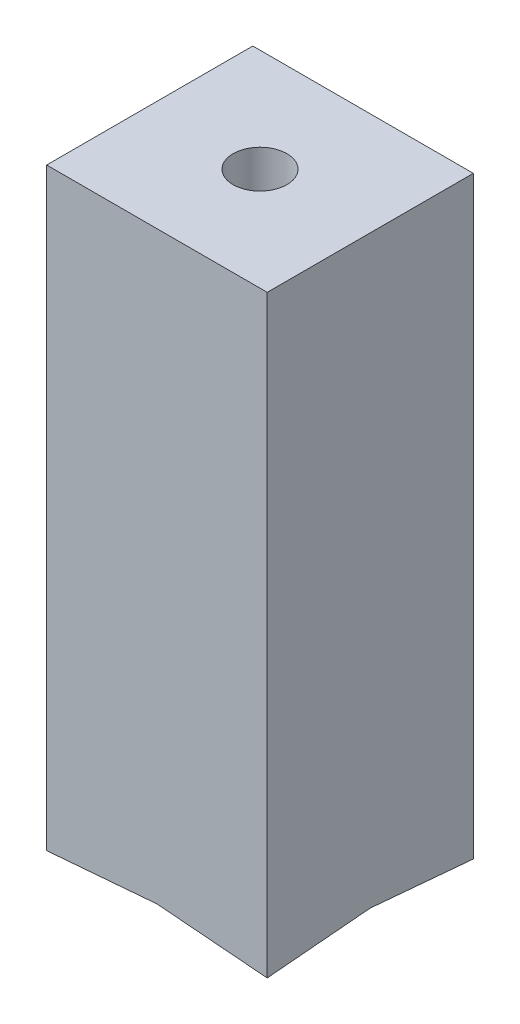
SolidWorks part; units mm, degrees
material "K110"
ref_plane "Front Plane" through (0, 0, 0) normal (0, 0, 1) x (1, 0, 0)
ref_plane "Top Plane" through (0, 0, 0) normal (0, 1, 0) x (1, 0, 0)
ref_plane "Right Plane" through (0, 0, 0) normal (1, 0, 0) x (0, 0, -1)
sketch "Sketch1" plane through (0, 0, 0) normal (0, 1, 0) x (1, 0, 0)
  line L1 (-10.25, -9.58) -> (10.25, -9.58)
  line L2 (-10.25, -9.58) -> (-10.25, 9.58)
  line L3 (-10.25, 9.58) -> (10.25, 9.58)
  line L4 (10.25, -9.58) -> (10.25, 9.58)
  line L5 (-10.25, -9.58) -> (10.25, 9.58) construction
  line L6 (-10.25, 9.58) -> (10.25, -9.58) construction
  point P0 (0, 0)
  dimension "D1" = 19.16
  dimension "D2" = 20.5
extrude "Boss-Extrude1" add sketch "Sketch1" against normal blind 55.2
sketch "Sketch5" plane through (10.25, 0, 0) normal (1, 0, 0) x (0, 0, -1)
  line L0 (-9.58, -55.2) -> (0, -54.3619)
  line L1 (0, -54.3619) -> (9.58, -55.2)
  line L2 (9.58, -55.2) -> (-9.58, -55.2)
  dimension "D1" = 5
extrude "Cut-Extrude3" cut sketch "Sketch5" against normal through all
sketch "Sketch6" plane through (0, 0, -9.58) normal (0, 0, -1) x (-1, 0, 0)
  line L0 (-10.25, -55.2) -> (0, -54.3619)
  line L1 (10.25, -54.3619) -> (-10.25, -54.3619) construction
  line L2 (0, -54.3619) -> (10.25, -55.2)
  line L3 (10.25, -55.2) -> (-10.25, -55.2)
  dimension "D1" = 4.675
extrude "Cut-Extrude4" cut sketch "Sketch6" against normal through all
hole_wizard "M6 Tapped Hole1" positions "Sketch9" profile "Sketch8" tap size "M6" standard "ISO"
sketch "Sketch9" plane through (0, 0, 0) normal (0, 1, 0) x (1, 0, 0)
  point P0 (0, 0)
sketch "Sketch8" plane through (0, 0, 0) normal (1, 0, 0) x (0, 0, 1)
  line L0 (0, 0) -> (0, 16.5022)
  line L1 (0, 16.5022) -> (2.5, 15)
  line L2 (2.5, 15) -> (2.5, 0)
  line L5 (2.5, 0) -> (0, 0)
  line L10 (0, 16.5022) -> (-2.5, 15) construction
  line L11 (0, -6.35) -> (0, 107.95) construction
  dimension "Tap Drill Dia." = 5
  dimension "Tap Drill Depth" = 15
  dimension "Drill Angle" = 118
cosmetic thread "Hole Thread1"
